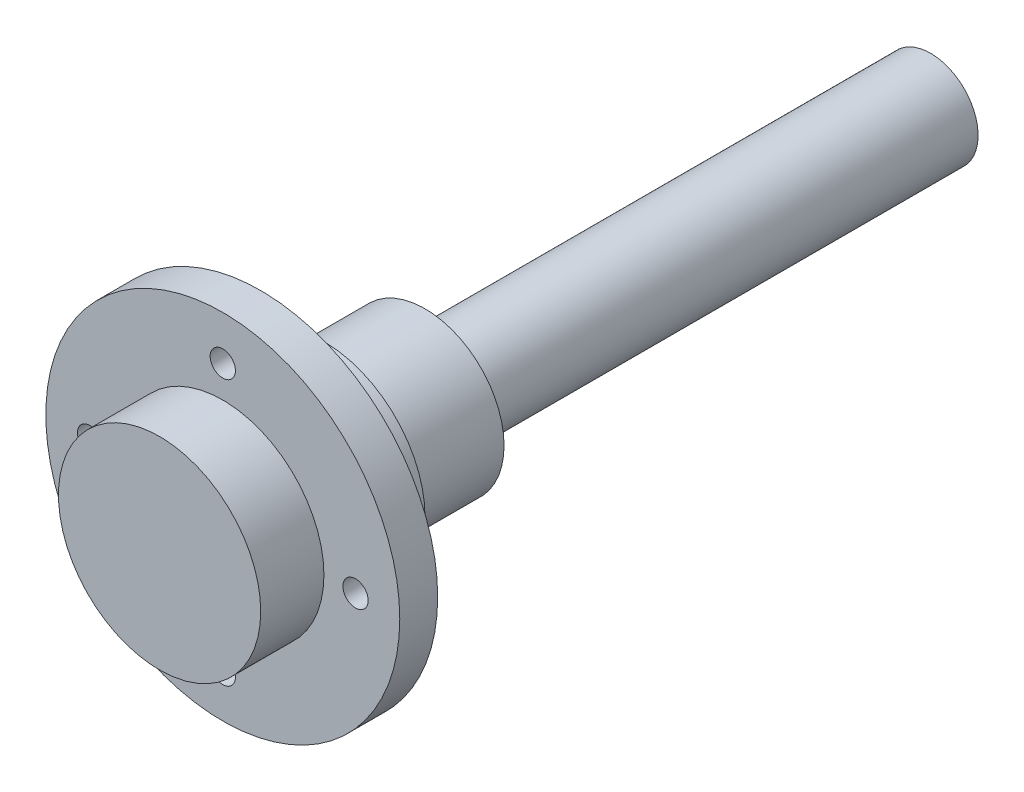
SolidWorks part; units mm, degrees
material "合金钢 (SS)"
ref_plane "前视基准面" through (0, 0, 0) normal (0, 0, 1) x (1, 0, 0)
ref_plane "上视基准面" through (0, 0, 0) normal (0, 1, 0) x (1, 0, 0)
ref_plane "右视基准面" through (0, 0, 0) normal (1, 0, 0) x (0, 0, -1)
sketch "草图1" plane through (0, 0, 0) normal (0, 0, 1) x (1, 0, 0)
  circle A0 centre (0, 0) radius 12.5
extrude "凸台-拉伸1" add sketch "草图1" along normal blind 16 contours A0
sketch "草图2" plane through (0, 0, 16) normal (0, 0, 1) x (1, 0, 0)
  circle A0 centre (0, 0) radius 16
extrude "凸台-拉伸2" add sketch "草图2" along normal blind 10
sketch "草图3" plane through (0, 0, 26) normal (0, 0, 1) x (1, 0, 0)
  circle A0 centre (0, 0) radius 28
extrude "凸台-拉伸3" add sketch "草图3" along normal blind 6 contours A0
sketch "草图6" plane through (0, 0, 26) normal (0, 0, -1) x (-1, 0, 0)
  circle A0 centre (0, 21) radius 2
extrude "切除-拉伸1" cut sketch "草图6" against normal blind 10
sketch "草图7" plane through (0, 0, 0) normal (0, 0, -1) x (-1, 0, 0)
  circle A0 centre (0, 0) radius 7.5
pattern_circular "阵列(圆周)2" count 4 over 360 about axis through (0, 0, 0) along (0, 0, 1) of "切除-拉伸1"
sketch "草图8" plane through (0, 0, 32) normal (0, 0, 1) x (1, 0, 0)
  circle A0 centre (0, 0) radius 16
extrude "凸台-拉伸5" add sketch "草图8" along normal blind 10
extrude "凸台-拉伸6" add sketch "草图7" along normal blind 80
